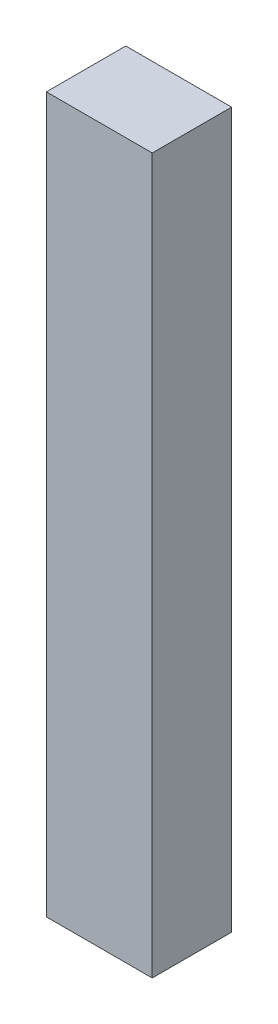
SolidWorks part; units mm, degrees
material "Pine"
ref_plane "Piano frontale" through (0, 0, 0) normal (0, 0, 1) x (1, 0, 0)
ref_plane "Piano superiore" through (0, 0, 0) normal (0, 1, 0) x (1, 0, 0)
ref_plane "Piano destro" through (0, 0, 0) normal (1, 0, 0) x (0, 0, -1)
sketch "Sketch1" plane through (0, 0, 0) normal (0, 0, 1) x (1, 0, 0)
  line L1 (0, 0) -> (2, 0)
  line L2 (0, 0) -> (0, 13.5)
  line L3 (0, 13.5) -> (2, 13.5)
  line L4 (2, 0) -> (2, 13.5)
  dimension "D1" = 2
  dimension "D2" = 13.5
extrude "Boss-Extrude1" add sketch "Sketch1" along normal blind 1.5 contours L4 L3 L2 L1
scale "Scale2" scale about origin uniform scaling yes scale factor 10
